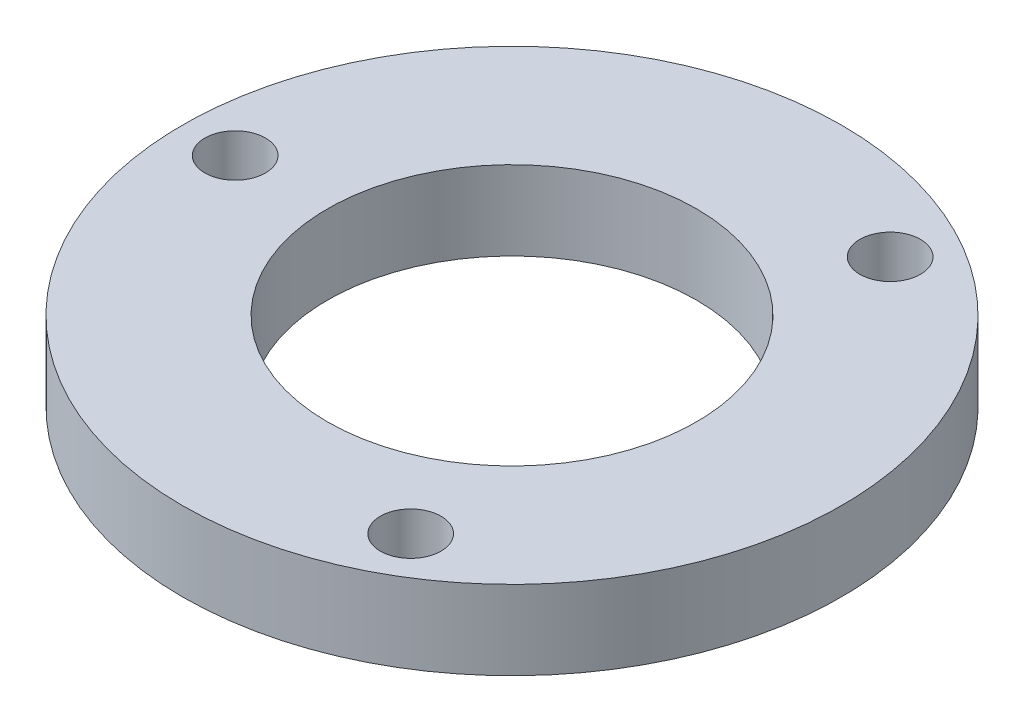
SolidWorks part; units mm, degrees
ref_plane "前视基准面" through (0, 0, 0) normal (0, 0, 1) x (1, 0, 0)
ref_plane "上视基准面" through (0, 0, 0) normal (0, 1, 0) x (1, 0, 0)
ref_plane "右视基准面" through (0, 0, 0) normal (1, 0, 0) x (0, 0, -1)
sketch "Sketch1" plane through (0, 0, 0) normal (0, 1, 0) x (1, 0, 0)
  circle A0 centre (0, 0) radius 12.5
  circle A1 centre (0, 0) radius 7
  dimension "D1" = 25
  dimension "D2" = 14
extrude "Boss-Extrude1" add sketch "Sketch1" along normal blind 3
sketch "Sketch2" plane through (0, 3, 0) normal (0, 1, 0) x (1, 0, 0)
  line L0 (0, 0) -> (-12.5, 0) construction
  circle A0 centre (0, 0) radius 10.5 construction
  circle A1 centre (0, 0) radius 12.5 construction
  point P7 (-10.5, 0)
  point P10 (5.25, -9.0933)
  point P11 (5.25, 9.0933)
  dimension "D1" = 21
sketch "Sketch3" plane through (0, 3, 0) normal (0, 1, 0) x (1, 0, 0)
  circle A0 centre (-10.5, 0) radius 1.15
  circle A1 centre (5.25, 9.0933) radius 1.15
  circle A2 centre (5.25, -9.0933) radius 1.15
  dimension "D1" = 2.3
  dimension "D2" = 3
extrude "Cut-Extrude1" cut sketch "Sketch3" against normal up to next
